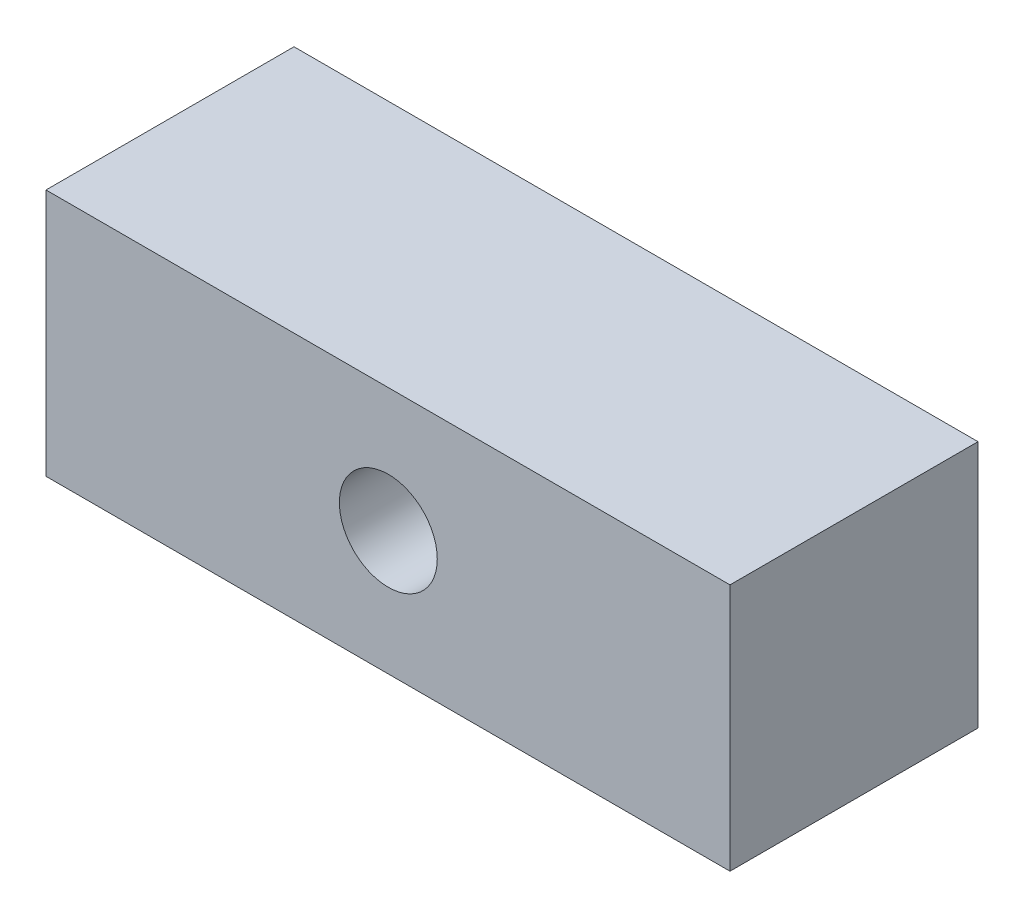
SolidWorks part; units mm, degrees
ref_plane "Front Plane" through (0, 0, 0) normal (0, 0, 1) x (1, 0, 0)
ref_plane "Top Plane" through (0, 0, 0) normal (0, 1, 0) x (1, 0, 0)
ref_plane "Right Plane" through (0, 0, 0) normal (1, 0, 0) x (0, 0, -1)
sketch "Sketch1" plane through (0, 0, 0) normal (0, 0, 1) x (1, 0, 0)
  line L1 (0, 0) -> (104.8, 0)
  line L2 (0, 0) -> (0, 38)
  line L3 (0, 38) -> (104.8, 38)
  line L4 (104.8, 0) -> (104.8, 38)
  circle A0 centre (52.45, 19) radius 7.5
  dimension "D5" = 15
  dimension "D1" = 104.8
  dimension "D2" = 38
  dimension "D3" = 52.45
  dimension "D4" = 19
extrude "Boss-Extrude1" add sketch "Sketch1" along normal blind 38
